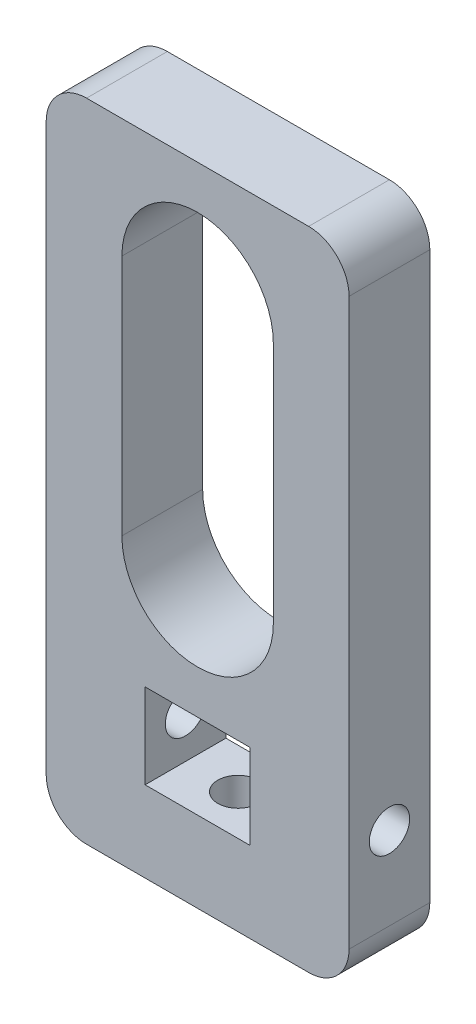
SolidWorks part; units mm, degrees
ref_plane "Front Plane" through (0, 0, 0) normal (0, 0, 1) x (1, 0, 0)
ref_plane "Top Plane" through (0, 0, 0) normal (0, 1, 0) x (1, 0, 0)
ref_plane "Right Plane" through (0, 0, 0) normal (1, 0, 0) x (0, 0, -1)
sketch "Sketch1" plane through (0, 0, 0) normal (0, 0, 1) x (1, 0, 0)
  line L2 (0, 0) -> (0, 66.04)
  line L3 (5.08, 71.12) -> (33.02, 71.12)
  line L4 (38.1, 0) -> (38.1, 66.04)
  line L5 (12.446, 0) -> (12.446, 10.668)
  line L6 (12.446, 10.668) -> (25.654, 10.668)
  line L7 (25.654, 10.668) -> (25.654, 0)
  line L9 (9.525, 56.134) -> (9.525, 25.654)
  line L10 (28.575, 56.134) -> (28.575, 25.654)
  line L11 (0, 0) -> (0, -5.08)
  line L12 (5.08, -10.16) -> (33.02, -10.16)
  line L13 (38.1, -5.08) -> (38.1, 0)
  line L14 (12.446, 0) -> (25.654, 0)
  line L15 (19.05, 71.12) -> (19.05, 56.134) construction
  line L16 (19.05, 56.134) -> (19.05, 25.654) construction
  line L17 (19.05, 10.668) -> (19.05, 25.654) construction
  line L18 (19.05, 0) -> (19.05, -10.16) construction
  line L19 (0, 10.668) -> (38.1, 10.668) construction
  arc A1 (9.525, 56.134) -> (28.575, 56.134) centre (19.05, 56.134) cw
  arc A2 (9.525, 25.654) -> (28.575, 25.654) centre (19.05, 25.654) ccw
  arc A3 (0, -5.08) -> (5.08, -10.16) centre (5.08, -5.08) ccw
  arc A4 (33.02, -10.16) -> (38.1, -5.08) centre (33.02, -5.08) ccw
  arc A5 (33.02, 71.12) -> (38.1, 66.04) centre (33.02, 66.04) cw
  arc A6 (0, 66.04) -> (5.08, 71.12) centre (5.08, 66.04) cw
  point P16 (19.05, 71.12)
  point P27 (0, 71.12)
  point P33 (19.05, 24.384)
  dimension "D5" = 9.525
  dimension "D7" = 5.08
  dimension "D1" = 13.208
  dimension "D2" = 71.12
  dimension "D3" = 10.668
  dimension "D4" = 10.16
  dimension "D6" = 30.48
  dimension "D8" = 38.1
extrude "Boss-Extrude2" add sketch "Sketch1" along normal blind 10.16
sketch "Sketch4" plane through (0, 0, 0) normal (-1, 0, 0) x (0, 0, 1)
  circle A0 centre (5.08, 5.334) radius 2.54
  point P2 (0, 0)
  dimension "D1" = 5.08
  dimension "D2" = 5.334
extrude "Cut-Extrude1" cut sketch "Sketch4" against normal blind 38.1
sketch "Sketch6" plane through (0, -10.16, 0) normal (0, -1, 0) x (1, 0, 0)
  line L0 (19.05, 5.08) -> (19.05, 10.16) construction
  line L1 (5.08, 10.16) -> (33.02, 10.16) construction
  line L2 (19.05, 5.08) -> (33.02, 5.08) construction
  line L3 (33.02, 10.16) -> (33.02, 0) construction
  circle A0 centre (19.05, 5.08) radius 2.54
  dimension "D1" = 5.08
extrude "Cut-Extrude2" cut sketch "Sketch6" against normal blind 10.16
